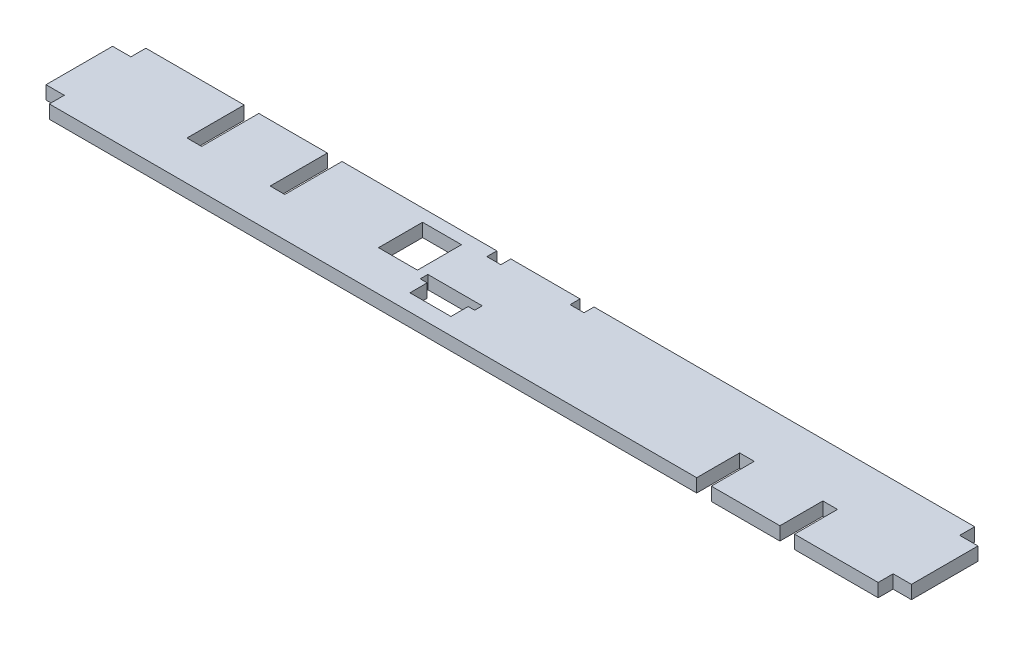
SolidWorks part; units mm, degrees
ref_plane "Спереди" through (0, 0, 0) normal (0, 0, 1) x (1, 0, 0)
ref_plane "Сверху" through (0, 0, 0) normal (0, 1, 0) x (1, 0, 0)
ref_plane "Справа" through (0, 0, 0) normal (1, 0, 0) x (0, 0, -1)
sketch "Эскиз1" plane through (0, 0, 0) normal (0, 1, 0) x (1, 0, 0)
  line L0 (-14.85, 14.4985) -> (5.95, 14.4985)
  line L1 (-124.5, -14.4985) -> (124.5, -14.4985)
  line L2 (-124.5, -14.4985) -> (-124.5, 14.4985)
  line L3 (-124.5, 14.4985) -> (-19.05, 14.4985)
  line L4 (124.5, -14.4985) -> (124.5, 14.4985)
  line L5 (-124.5, -14.4985) -> (124.5, 14.4985) construction
  line L6 (-124.5, 14.4985) -> (124.5, -14.4985) construction
  line L7 (-19.05, 14.4985) -> (-18.95, 14.4985) construction
  line L8 (-19.05, 14.4985) -> (-19.05, 11.4985)
  line L9 (-19.05, 11.4985) -> (-14.85, 11.4985)
  line L10 (-14.85, 14.4985) -> (-14.85, 11.4985)
  line L11 (5.95, 11.4985) -> (10.15, 11.4985)
  line L12 (5.95, 14.4985) -> (5.95, 11.4985)
  line L13 (10.15, 14.4985) -> (10.15, 11.4985)
  line L14 (10.15, 14.4985) -> (124.5, 14.4985)
  point P0 (0, 0)
  dimension "D1" = 28.997
  dimension "D2" = 249
  dimension "D3" = 4.2
  dimension "D4" = 3
  dimension "D5" = 0.1
  dimension "D6" = 2
extrude "Бобышка-Вытянуть1" add sketch "Эскиз1" along normal blind 4
sketch "Эскиз2" plane through (124.5, 0, 0) normal (1, 0, 0) x (0, 0, -1)
  line L0 (14.4985, 4) -> (-14.4985, 0) construction
  line L2 (-10, 4) -> (10, 4)
  line L3 (-10, 4) -> (-10, 0)
  line L4 (-10, 0) -> (10, 0)
  line L5 (10, 4) -> (10, 0)
  line L6 (-10, 4) -> (10, 0) construction
  line L7 (-10, 0) -> (10, 4) construction
  point P4 (0, 2)
  dimension "D1" = 4
  dimension "D2" = 20
extrude "Бобышка-Вытянуть2" add sketch "Эскиз2" along normal blind 5.5
mirror "Mirror1" about plane through (0, 0, 0) normal (1, 0, 0) of "Бобышка-Вытянуть2"
sketch "Sketch1" plane through (0, 4, 0) normal (0, 1, 0) x (1, 0, 0)
  line L0 (-19.05, 14.4985) -> (-124.5, 14.4985) construction
  line L1 (-69.9638, -2.6921) -> (-65.5638, -2.6921)
  line L2 (-69.9638, -2.6921) -> (-69.9638, 14.4985)
  line L3 (-69.9638, 14.4985) -> (-65.5638, 14.4985)
  line L4 (-65.5638, -2.6921) -> (-65.5638, 14.4985)
  line L5 (-69.9638, -2.5015) -> (-69.7638, -2.5015) construction
  dimension "D1" = 4.4
  dimension "D2" = 0.2
extrude "Cut-Extrude1" cut sketch "Sketch1" against normal blind 10
pattern_linear "LPattern1" count 2 spacing 25 along (-1, 0, 0) of "Cut-Extrude1"
sketch "Sketch2" plane through (0, 0, 0) normal (0, -1, 0) x (1, 0, 0)
  line L1 (-23.2847, 1.9997) -> (-6.9316, 1.9997)
  line L2 (-23.2847, 1.9997) -> (-23.2847, 4.289)
  line L3 (-23.2847, 4.289) -> (-6.9316, 4.289)
  line L4 (-6.9316, 1.9997) -> (-6.9316, 4.289)
  line L5 (-8.871, 9.4717) -> (-21.1883, 9.4717)
  line L6 (-8.871, 9.4717) -> (-8.871, 4.289)
  line L7 (-8.871, 4.289) -> (-21.1883, 4.289)
  line L8 (-21.1883, 9.4717) -> (-21.1883, 4.289)
sketch "Sketch3" plane through (0, 0, 0) normal (0, 1, 0) x (1, 0, 0)
  line L1 (-37.6507, -2.449) -> (-25.9648, -2.449)
  line L2 (-37.6507, -2.449) -> (-37.6507, 10.7875)
  line L3 (-37.6507, 10.7875) -> (-25.9648, 10.7875)
  line L4 (-25.9648, -2.449) -> (-25.9648, 10.7875)
extrude "Cut-Extrude3" cut sketch "Sketch3" along normal blind 10
extrude "Cut-Extrude4" cut sketch "Sketch2" against normal blind 10 contours L1 L4 L3 L2 | L5 L8 L3 L6
sketch "Sketch4" plane through (0, 4, 0) normal (0, 1, 0) x (1, 0, 0)
  line L0 (-124.5, -14.4985) -> (124.5, -14.4985) construction
  line L1 (74.3858, -1.6015) -> (69.9858, -1.6015)
  line L2 (74.3858, -1.6015) -> (74.3858, -14.4985)
  line L3 (74.3858, -14.4985) -> (69.9858, -14.4985)
  line L4 (69.9858, -1.6015) -> (69.9858, -14.4985)
  line L5 (74.3858, -1.6015) -> (74.1858, -1.6015) construction
  dimension "D1" = 4.4
  dimension "D2" = 0.2
extrude "Cut-Extrude5" cut sketch "Sketch4" against normal blind 10
pattern_linear "LPattern2" count 2 spacing 25 along (1, 0, 0) of "Cut-Extrude5"
